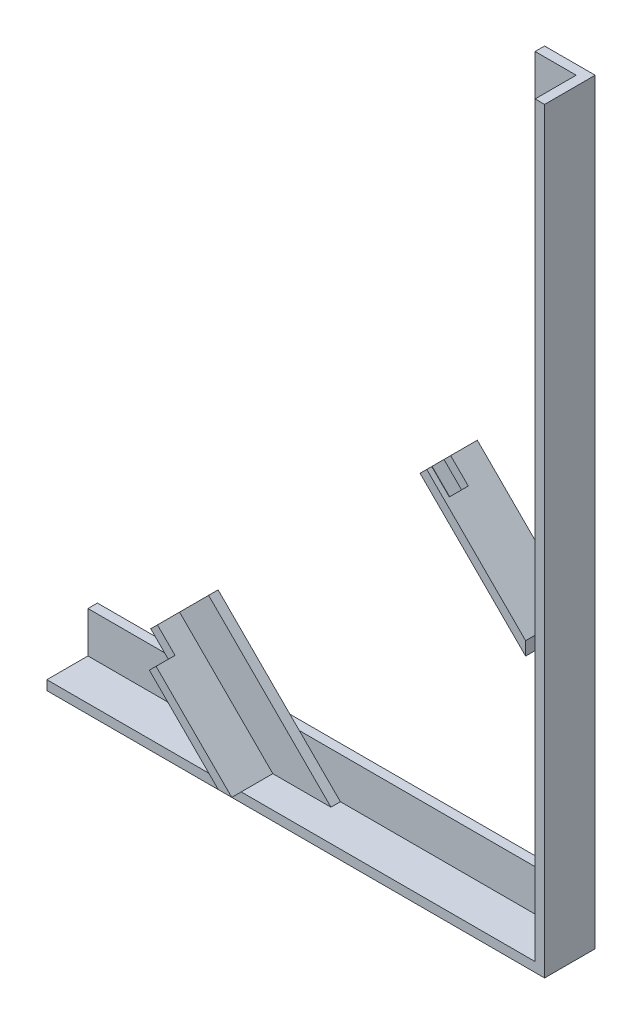
SolidWorks part; units mm, degrees
ref_plane "Alzado" through (0, 0, 0) normal (0, 0, 1) x (1, 0, 0)
ref_plane "Planta" through (0, 0, 0) normal (0, 1, 0) x (1, 0, 0)
ref_plane "Vista lateral" through (0, 0, 0) normal (1, 0, 0) x (0, 0, -1)
sketch "Croquis1" plane through (0, 0, 0) normal (0, 0, 1) x (1, 0, 0)
  line L0 (0, 0) -> (0, 760)
  line L1 (0, 0) -> (-500, 0)
  line L2 (-9.525, 9.525) -> (-500, 9.525)
  line L3 (-9.525, 9.525) -> (-9.525, 760)
  line L4 (-9.525, 760) -> (0, 760)
  line L5 (-500, 9.525) -> (-500, 0)
  dimension "D1" = 760
  dimension "D2" = 500
  dimension "D3" = 9.525
extrude "Saliente-Extruir1" add sketch "Croquis1" along normal blind 50.8
sketch "Croquis2" plane through (0, 0, 0) normal (0, 0, -1) x (-1, 0, 0)
  line L0 (0, 760) -> (0, 0)
  line L1 (0, 0) -> (500, 0)
  line L2 (50.8, 760) -> (50.8, 50.8)
  line L3 (50.8, 50.8) -> (500, 50.8)
  line L4 (500, 0) -> (500, 50.8)
  line L5 (0, 760) -> (50.8, 760)
  dimension "D1" = 50.8
extrude "Saliente-Extruir2" add sketch "Croquis2" against normal blind 9.525
sketch "Croquis3" plane through (0, 0, 9.525) normal (0, 0, 1) x (1, 0, 0)
  line L0 (-9.525, 280) -> (-115.591, 386.066)
  line L1 (-9.525, 760) -> (-9.525, 9.525) construction
  line L2 (-500, 0) -> (0, 0) construction
  line L3 (-9.525, 293.4704) -> (-108.8558, 392.8012)
  line L4 (-9.525, 280) -> (-9.525, 293.4704)
  line L5 (-304.7354, 9.525) -> (-318.2058, 9.525)
  line L6 (-2.7898, 286.7352) -> (-108.8558, 392.8012) construction
  line L7 (-108.8558, 392.8012) -> (-115.591, 386.066)
  line L8 (-115.591, 386.066) -> (-398.4337, 103.2233) construction
  line L9 (-398.4337, 103.2233) -> (-304.7354, 9.525)
  line L10 (-9.525, 9.525) -> (-500, 9.525) construction
  line L11 (-9.525, 9.525) -> (-500, 9.525) construction
  line L12 (-405.1689, 96.4881) -> (-318.2058, 9.525)
  line L13 (-398.4337, 103.2233) -> (-405.1689, 96.4881)
  line L15 (-405.1689, 96.4881) -> (-311.4706, 2.7898) construction
  dimension "D1" = 45
  dimension "D2" = 150
  dimension "D3" = 280
  dimension "D5" = 45
  dimension "D6" = 400
  dimension "D4" = 9.525
  dimension "D7" = 9.525
extrude "Saliente-Extruir3" add sketch "Croquis3" along normal blind 50.8
sketch "Croquis4" plane through (0, 0, 9.525) normal (0, 0, 1) x (1, 0, 0)
  line L0 (-9.525, 280) -> (-115.591, 386.066)
  line L1 (-9.525, 221.6283) -> (-144.7768, 356.8802)
  line L2 (-38.7108, 250.8142) -> (-144.7768, 356.8802) construction
  line L3 (-9.525, 280) -> (-9.525, 9.525) construction
  line L4 (-144.7768, 356.8802) -> (-115.591, 386.066)
  line L5 (-9.525, 280) -> (-9.525, 221.6283)
  line L6 (-398.4337, 103.2233) -> (-304.7354, 9.525)
  line L7 (-369.2479, 132.4091) -> (-246.3638, 9.525)
  line L8 (-369.2479, 132.4091) -> (-275.5496, 38.7108) construction
  line L10 (-398.4337, 103.2233) -> (-369.2479, 132.4091)
  line L11 (-304.7354, 9.525) -> (-246.3638, 9.525)
  dimension "D1" = 41.275
  dimension "D2" = 41.275
extrude "Saliente-Extruir4" add sketch "Croquis4" along normal blind 9.525
sketch "Croquis5" plane through (-250.8285, 250.8285, 0) normal (-0.7071, 0.7071, 0) x (0, 0, 1)
  line L0 (19.05, 191.2547) -> (19.05, 200.7797) construction
  line L1 (60.325, 200.7797) -> (9.525, 200.7797) construction
  line L2 (60.325, 191.2547) -> (19.05, 191.2547) construction
  line L4 (9.525, 149.9797) -> (9.525, -167.4703) construction
  line L5 (36.275, 200.7797) -> (55.325, 200.7797)
  line L6 (36.275, 200.7797) -> (36.275, 191.2547)
  line L7 (36.275, 191.2547) -> (55.325, 191.2547)
  line L8 (55.325, 200.7797) -> (55.325, 191.2547)
  line L9 (60.325, 200.7797) -> (60.325, 191.2547) construction
  line L11 (9.525, -8.7453) -> (98.6206, -8.7453) construction
  line L12 (41.275, -218.2703) -> (60.325, -208.7453) construction
  line L13 (41.275, -208.7453) -> (60.325, -218.2703) construction
  line L14 (60.325, -213.5078) -> (19.05, -213.5078) construction
  line L15 (19.05, -208.7453) -> (19.05, -218.2703) construction
  line L16 (60.325, -208.7453) -> (60.325, -218.2703)
  line L17 (41.275, -218.2703) -> (60.325, -218.2703)
  line L18 (41.275, -208.7453) -> (41.275, -218.2703)
  line L19 (41.275, -208.7453) -> (60.325, -208.7453)
  point P9 (50.8, 196.0172)
  point P28 (50.8, -213.5078)
  dimension "D1" = 19.05
  dimension "D2" = 5
extrude "Cortar-Extruir1" cut sketch "Croquis5" against normal blind 25
